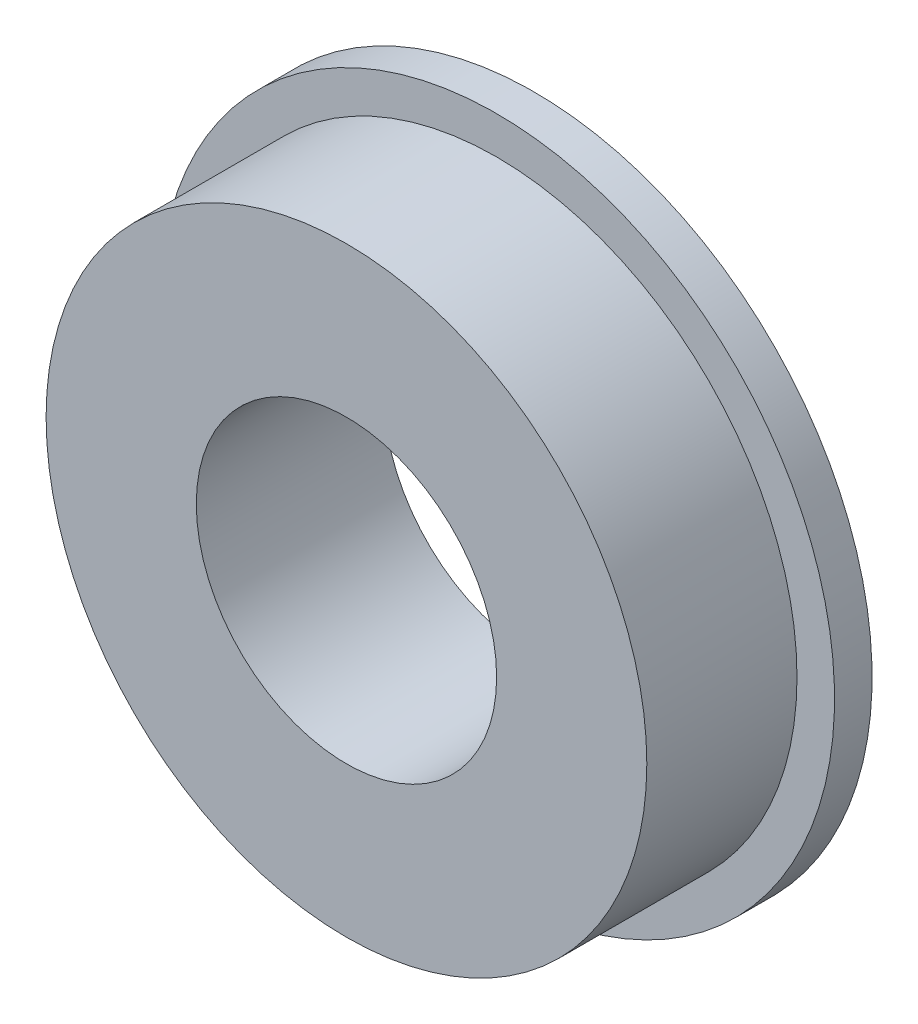
SolidWorks part; units mm, degrees
ref_plane "Front Plane" through (0, 0, 0) normal (0, 0, 1) x (1, 0, 0)
ref_plane "Top Plane" through (0, 0, 0) normal (0, 1, 0) x (1, 0, 0)
ref_plane "Right Plane" through (0, 0, 0) normal (1, 0, 0) x (0, 0, -1)
sketch "Sketch1" plane through (0, 0, 0) normal (0, 1, 0) x (1, 0, 0)
  line L0 (4, 0) -> (9, 0)
  line L1 (9, 0) -> (9, -1)
  line L2 (9, -1) -> (8, -1)
  line L3 (8, -1) -> (8, -5)
  line L4 (8, -5) -> (4, -5)
  line L5 (4, -5) -> (4, 0)
  line L6 (4, 0) -> (0, 0) construction
  line L7 (0, 0) -> (0, -5) construction
  line L8 (0, -5) -> (4, -5) construction
  dimension "D1" = 4
  dimension "D2" = 8
  dimension "D3" = 9
  dimension "D4" = 5
  dimension "D5" = 1
revolve "Revolve1" add sketch "Sketch1" angle 360 about L7
